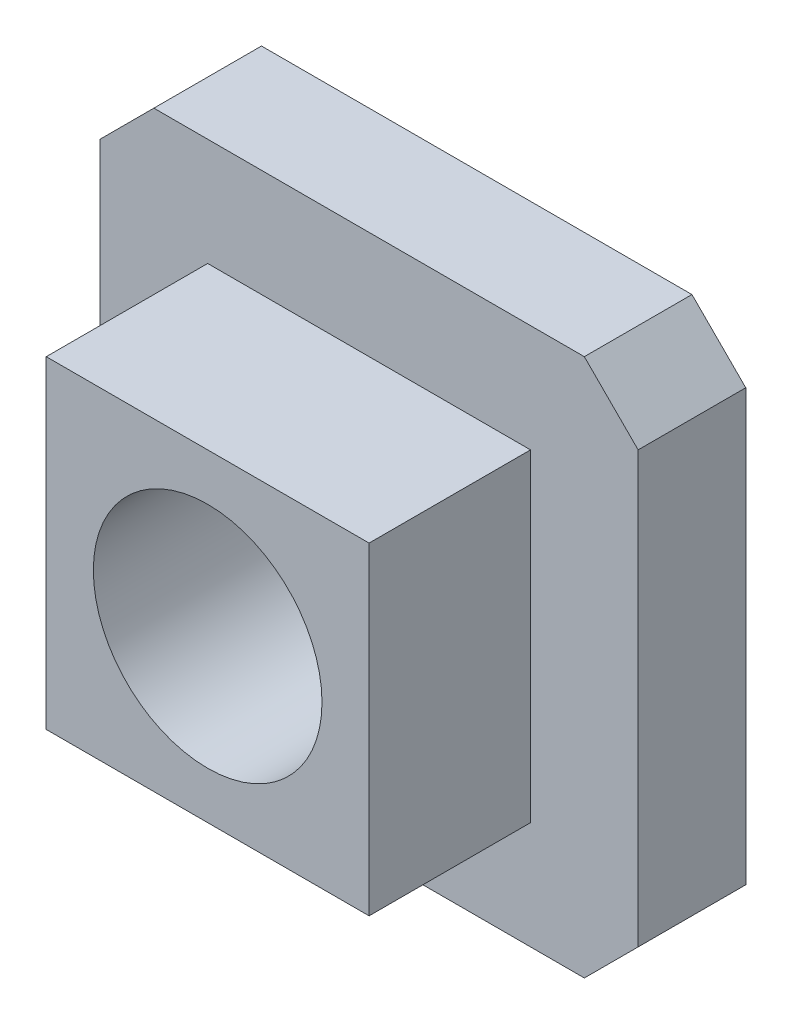
SolidWorks part; units mm, degrees
material "6061 Alloy"
ref_plane "Front Plane" through (0, 0, 0) normal (0, 0, 1) x (1, 0, 0)
ref_plane "Top Plane" through (0, 0, 0) normal (0, 1, 0) x (1, 0, 0)
ref_plane "Right Plane" through (0, 0, 0) normal (1, 0, 0) x (0, 0, -1)
sketch "Sketch1" plane through (0, 0, 0) normal (0, 0, 1) x (1, 0, 0)
  line L1 (15.875, -15.875) -> (-15.875, -15.875)
  line L2 (15.875, -15.875) -> (15.875, 15.875)
  line L3 (15.875, 15.875) -> (-15.875, 15.875)
  line L4 (-15.875, -15.875) -> (-15.875, 15.875)
  line L5 (15.875, -15.875) -> (-15.875, 15.875) construction
  line L6 (15.875, 15.875) -> (-15.875, -15.875) construction
  point P0 (0, 0)
  dimension "D1" = 31.75
extrude "Boss-Extrude1" add sketch "Sketch1" along normal mid plane 6.35
sketch "Sketch4" plane through (0, 0, 3.175) normal (0, 0, 1) x (1, 0, 0)
  line L1 (9.525, -9.525) -> (-9.525, -9.525)
  line L2 (9.525, -9.525) -> (9.525, 9.525)
  line L3 (9.525, 9.525) -> (-9.525, 9.525)
  line L4 (-9.525, -9.525) -> (-9.525, 9.525)
  line L5 (9.525, -9.525) -> (-9.525, 9.525) construction
  line L6 (9.525, 9.525) -> (-9.525, -9.525) construction
  point P0 (0, 0)
  dimension "D1" = 19.05
extrude "Boss-Extrude2" add sketch "Sketch4" along normal blind 9.525
hole_wizard "5/8-11 Tapped Hole2" positions "Sketch5" profile "Sketch6" tap size "5/8-11" standard "ANSI Inch" end condition through all
sketch "Sketch5" plane through (0, 0, -3.175) normal (0, 0, -1) x (-1, 0, 0)
  point P0 (0, 0)
sketch "Sketch6" plane through (0, 0, -3.175) normal (1, 0, 0) x (0, 1, 0)
  line L0 (0, 0) -> (0, 15.875)
  line L1 (0, 15.875) -> (6.7462, 15.875)
  line L2 (6.7462, 15.875) -> (6.7462, 0)
  line L5 (6.7462, 0) -> (0, 0)
  line L11 (0, -6.35) -> (0, 107.95) construction
  dimension "Thru Tap Drill Dia." = 13.4925
  dimension "Thru Tap Drill Depth" = 15.875
cosmetic thread "Hole Thread2" parameters "D2"=15.875
fillet "Fillet1" [suppressed] radius 3.175
chamfer "Chamfer1" distance 3.175 angle 45 4 edges at (15.875, 15.875, 0) (-15.875, 15.875, 0) (-15.875, -15.875, 0) (15.875, -15.875, 0)
